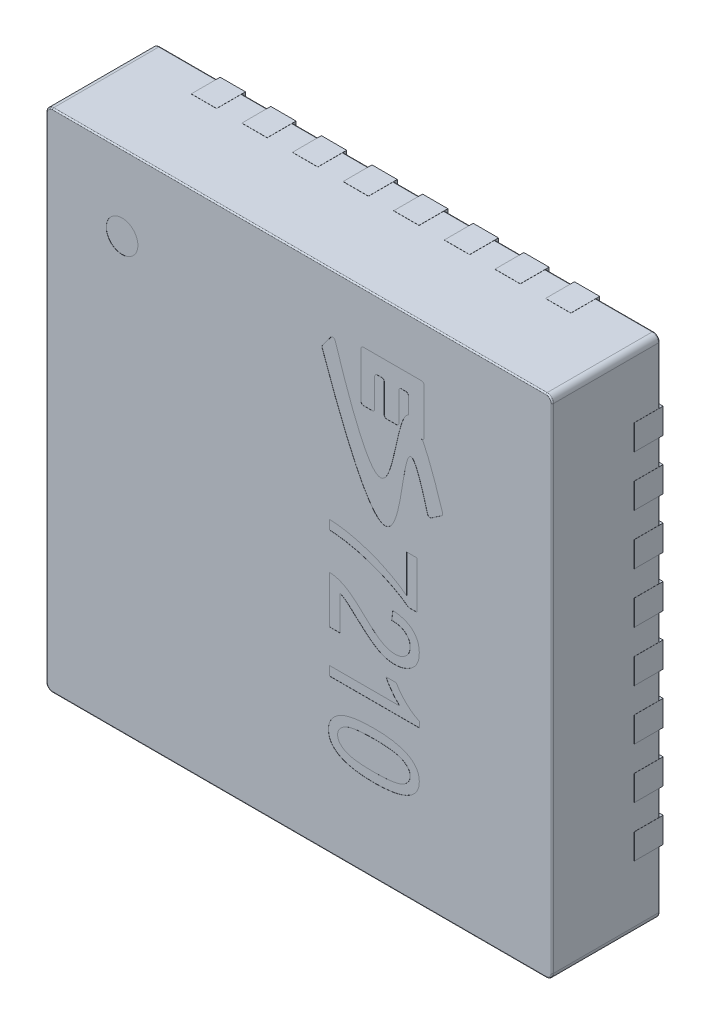
SolidWorks part; units mm, degrees
other "ES7210" parameters "D5"=0.3678, "D1"=3.1308, "D2"=3.0402, "D3"=0.4115, "D4"=0.3, "D6"=0.3296, "D7"=0.2637, "D8"=0.9806, "D10"=0.4, "D11"=0.25, "D9"=4
ref_plane "Front Plane" through (0, 0, 0) normal (0, 0, 1) x (1, 0, 0)
ref_plane "Top Plane" through (0, 0, 0) normal (0, 1, 0) x (1, 0, 0)
ref_plane "Right Plane" through (0, 0, 0) normal (1, 0, 0) x (0, 0, -1)
sketch "Sketch1" plane through (0, 0, 0) normal (0, 1, 0) x (1, 0, 0)
  line L1 (-2, -2) -> (2, -2)
  line L2 (-2, -2) -> (-2, 2)
  line L3 (-2, 2) -> (2, 2)
  line L4 (2, -2) -> (2, 2)
  line L5 (-2, -2) -> (2, 2) construction
  line L6 (-2, 2) -> (2, -2) construction
  point P0 (0, 0)
  dimension "D1" = 4
  dimension "D2" = 4
extrude "Boss-Extrude1" add sketch "Sketch1" along normal blind 0.85
fillet "Fillet1" radius 0.05 4 edges at (2, 0.425, -2) (2, 0.425, 2) (-2, 0.425, 2) (-2, 0.425, -2)
fillet "Fillet2" radius 0.01 16 edges at (1.9854, 0.85, 1.9854) (0, 0.85, 2) (-1.9854, 0.85, 1.9854) (-2, 0.85, 0) (-1.9854, 0.85, -1.9854) (0, 0.85, -2) (1.9854, 0.85, -1.9854) (2, 0.85, 0) (2, 0, 0) (1.9854, 0, -1.9854) (0, 0, -2) (1.9854, 0, 1.9854) (0, 0, 2) (-1.9854, 0, 1.9854) (-2, 0, 0) (-1.9854, 0, -1.9854)
sketch "Sketch2" plane through (0, 0, 0) normal (0, -1, 0) x (1, 0, 0)
  line L0 (1.1, 1.4) -> (1.4, 1.1)
  line L1 (-1.35, -1.4) -> (1.35, -1.4)
  line L2 (-1.4, -1.35) -> (-1.4, 1.35)
  line L3 (-1.35, 1.4) -> (1.1, 1.4)
  line L4 (1.4, -1.35) -> (1.4, 1.1)
  line L5 (-1.3854, -1.3854) -> (1.4, 1.4) construction
  line L6 (-1.3854, 1.3854) -> (1.3854, -1.3854) construction
  line L7 (1.1, 1.4) -> (1.4, 1.4) construction
  line L8 (1.4, 1.1) -> (1.4, 1.4) construction
  line L9 (-1.4, 1.4) -> (-1.35, 1.4) construction
  line L10 (-1.4, 1.4) -> (-1.3854, 1.3854) construction
  line L11 (-1.4, 1.35) -> (-1.4, 1.4) construction
  line L12 (-1.4, -1.4) -> (-1.4, -1.35) construction
  line L13 (-1.4, -1.4) -> (-1.3854, -1.3854) construction
  line L14 (-1.4, -1.4) -> (-1.35, -1.4) construction
  line L15 (1.4, -1.4) -> (1.4, -1.35) construction
  line L16 (1.3854, -1.3854) -> (1.4, -1.4) construction
  line L17 (1.35, -1.4) -> (1.4, -1.4) construction
  line L18 (0, -1000) -> (0, 49000) construction
  line L23 (-0.3, 2.001) -> (-0.1, 2.001)
  line L24 (-0.3, 2.001) -> (-0.3, 1.701)
  line L25 (-0.3, 1.701) -> (-0.1, 1.701)
  line L26 (-0.1, 2.001) -> (-0.1, 1.701)
  line L27 (-0.3, 2.001) -> (-0.1, 1.701) construction
  line L28 (-0.3, 1.701) -> (-0.1, 2.001) construction
  line L30 (-0.7, 2.001) -> (-0.7, 1.701)
  line L31 (-0.7, 2.001) -> (-0.5, 2.001)
  line L32 (-0.5, 2.001) -> (-0.5, 1.701)
  line L33 (-0.7, 1.701) -> (-0.5, 1.701)
  line L34 (-0.7, 1.701) -> (-0.5, 2.001) construction
  line L35 (-0.7, 2.001) -> (-0.5, 1.701) construction
  line L36 (-1.1, 2.001) -> (-1.1, 1.701)
  line L37 (-1.1, 2.001) -> (-0.9, 2.001)
  line L38 (-0.9, 2.001) -> (-0.9, 1.701)
  line L39 (-1.1, 1.701) -> (-0.9, 1.701)
  line L40 (-1.1, 1.701) -> (-0.9, 2.001) construction
  line L41 (-1.1, 2.001) -> (-0.9, 1.701) construction
  line L42 (-1.5, 2.001) -> (-1.5, 1.701)
  line L43 (-1.5, 2.001) -> (-1.3, 2.001)
  line L44 (-1.3, 2.001) -> (-1.3, 1.701)
  line L45 (-1.5, 1.701) -> (-1.3, 1.701)
  line L46 (-1.5, 1.701) -> (-1.3, 2.001) construction
  line L47 (-1.5, 2.001) -> (-1.3, 1.701) construction
  line L48 (-0.3, 2.001) -> (-0.7, 2.001) construction
  line L162 (-1000, 0) -> (49000, 0) construction
  line L163 (-2, 2) -> (2, 2) construction
  line L164 (0.3, 2.001) -> (0.7, 2.001) construction
  line L165 (1.5, 2.001) -> (1.3, 1.701) construction
  line L166 (1.5, 1.701) -> (1.3, 2.001) construction
  line L167 (1.1, 2.001) -> (0.9, 1.701) construction
  line L168 (1.1, 1.701) -> (0.9, 2.001) construction
  line L169 (0.7, 2.001) -> (0.5, 1.701) construction
  line L170 (0.7, 1.701) -> (0.5, 2.001) construction
  line L171 (0.3, 1.701) -> (0.1, 2.001) construction
  line L172 (0.3, 2.001) -> (0.1, 1.701) construction
  line L173 (1.5, 1.701) -> (1.3, 1.701)
  line L174 (1.3, 2.001) -> (1.3, 1.701)
  line L175 (1.5, 2.001) -> (1.3, 2.001)
  line L176 (1.5, 2.001) -> (1.5, 1.701)
  line L177 (1.1, 1.701) -> (0.9, 1.701)
  line L178 (0.9, 2.001) -> (0.9, 1.701)
  line L179 (1.1, 2.001) -> (0.9, 2.001)
  line L180 (1.1, 2.001) -> (1.1, 1.701)
  line L181 (0.7, 1.701) -> (0.5, 1.701)
  line L182 (0.5, 2.001) -> (0.5, 1.701)
  line L183 (0.7, 2.001) -> (0.5, 2.001)
  line L184 (0.7, 2.001) -> (0.7, 1.701)
  line L185 (0.1, 2.001) -> (0.1, 1.701)
  line L186 (0.3, 1.701) -> (0.1, 1.701)
  line L187 (0.3, 2.001) -> (0.3, 1.701)
  line L188 (0.3, 2.001) -> (0.1, 2.001)
  line L189 (0.3, -2.001) -> (0.1, -1.701) construction
  line L190 (0.3, -1.701) -> (0.1, -2.001) construction
  line L191 (0.7, -1.701) -> (0.5, -2.001) construction
  line L192 (0.7, -2.001) -> (0.5, -1.701) construction
  line L193 (1.1, -1.701) -> (0.9, -2.001) construction
  line L194 (1.1, -2.001) -> (0.9, -1.701) construction
  line L195 (1.5, -1.701) -> (1.3, -2.001) construction
  line L196 (1.5, -2.001) -> (1.3, -1.701) construction
  line L197 (0.3, -2.001) -> (0.7, -2.001) construction
  line L198 (-0.3, -2.001) -> (-0.7, -2.001) construction
  line L199 (-1.5, -2.001) -> (-1.3, -1.701) construction
  line L200 (-1.5, -1.701) -> (-1.3, -2.001) construction
  line L201 (-1.1, -2.001) -> (-0.9, -1.701) construction
  line L202 (-1.1, -1.701) -> (-0.9, -2.001) construction
  line L203 (-0.7, -2.001) -> (-0.5, -1.701) construction
  line L204 (-0.7, -1.701) -> (-0.5, -2.001) construction
  line L205 (-0.3, -1.701) -> (-0.1, -2.001) construction
  line L206 (-0.3, -2.001) -> (-0.1, -1.701) construction
  line L207 (0.3, -2.001) -> (0.1, -2.001)
  line L208 (0.3, -2.001) -> (0.3, -1.701)
  line L209 (0.3, -1.701) -> (0.1, -1.701)
  line L210 (0.1, -2.001) -> (0.1, -1.701)
  line L211 (0.7, -2.001) -> (0.7, -1.701)
  line L212 (0.7, -2.001) -> (0.5, -2.001)
  line L213 (0.5, -2.001) -> (0.5, -1.701)
  line L214 (0.7, -1.701) -> (0.5, -1.701)
  line L215 (1.1, -2.001) -> (1.1, -1.701)
  line L216 (1.1, -2.001) -> (0.9, -2.001)
  line L217 (0.9, -2.001) -> (0.9, -1.701)
  line L218 (1.1, -1.701) -> (0.9, -1.701)
  line L219 (1.5, -2.001) -> (1.5, -1.701)
  line L220 (1.5, -2.001) -> (1.3, -2.001)
  line L221 (1.3, -2.001) -> (1.3, -1.701)
  line L222 (1.5, -1.701) -> (1.3, -1.701)
  line L223 (-1.5, -1.701) -> (-1.3, -1.701)
  line L224 (-1.3, -2.001) -> (-1.3, -1.701)
  line L225 (-1.5, -2.001) -> (-1.3, -2.001)
  line L226 (-1.5, -2.001) -> (-1.5, -1.701)
  line L227 (-1.1, -1.701) -> (-0.9, -1.701)
  line L228 (-0.9, -2.001) -> (-0.9, -1.701)
  line L229 (-1.1, -2.001) -> (-0.9, -2.001)
  line L230 (-1.1, -2.001) -> (-1.1, -1.701)
  line L231 (-0.7, -1.701) -> (-0.5, -1.701)
  line L232 (-0.5, -2.001) -> (-0.5, -1.701)
  line L233 (-0.7, -2.001) -> (-0.5, -2.001)
  line L234 (-0.7, -2.001) -> (-0.7, -1.701)
  line L235 (-0.1, -2.001) -> (-0.1, -1.701)
  line L236 (-0.3, -1.701) -> (-0.1, -1.701)
  line L237 (-0.3, -2.001) -> (-0.3, -1.701)
  line L238 (-0.3, -2.001) -> (-0.1, -2.001)
  line L239 (2.001, 0.3) -> (1.701, 0.1) construction
  line L240 (1.701, 0.3) -> (2.001, 0.1) construction
  line L241 (1.701, 0.7) -> (2.001, 0.5) construction
  line L242 (2.001, 0.7) -> (1.701, 0.5) construction
  line L243 (1.701, 1.1) -> (2.001, 0.9) construction
  line L244 (2.001, 1.1) -> (1.701, 0.9) construction
  line L245 (1.701, 1.5) -> (2.001, 1.3) construction
  line L246 (2.001, 1.5) -> (1.701, 1.3) construction
  line L247 (2.001, 0.3) -> (2.001, 0.7) construction
  line L248 (2.001, -0.3) -> (2.001, -0.7) construction
  line L249 (2.001, -1.5) -> (1.701, -1.3) construction
  line L250 (1.701, -1.5) -> (2.001, -1.3) construction
  line L251 (2.001, -1.1) -> (1.701, -0.9) construction
  line L252 (1.701, -1.1) -> (2.001, -0.9) construction
  line L253 (2.001, -0.7) -> (1.701, -0.5) construction
  line L254 (1.701, -0.7) -> (2.001, -0.5) construction
  line L255 (1.701, -0.3) -> (2.001, -0.1) construction
  line L256 (2.001, -0.3) -> (1.701, -0.1) construction
  line L257 (2.001, 0.3) -> (2.001, 0.1)
  line L258 (2.001, 0.3) -> (1.701, 0.3)
  line L259 (1.701, 0.3) -> (1.701, 0.1)
  line L260 (2.001, 0.1) -> (1.701, 0.1)
  line L261 (2.001, 0.7) -> (1.701, 0.7)
  line L262 (2.001, 0.7) -> (2.001, 0.5)
  line L263 (2.001, 0.5) -> (1.701, 0.5)
  line L264 (1.701, 0.7) -> (1.701, 0.5)
  line L265 (2.001, 1.1) -> (1.701, 1.1)
  line L266 (2.001, 1.1) -> (2.001, 0.9)
  line L267 (2.001, 0.9) -> (1.701, 0.9)
  line L268 (1.701, 1.1) -> (1.701, 0.9)
  line L269 (2.001, 1.5) -> (1.701, 1.5)
  line L270 (2.001, 1.5) -> (2.001, 1.3)
  line L271 (2.001, 1.3) -> (1.701, 1.3)
  line L272 (1.701, 1.5) -> (1.701, 1.3)
  line L273 (1.701, -1.5) -> (1.701, -1.3)
  line L274 (2.001, -1.3) -> (1.701, -1.3)
  line L275 (2.001, -1.5) -> (2.001, -1.3)
  line L276 (2.001, -1.5) -> (1.701, -1.5)
  line L277 (1.701, -1.1) -> (1.701, -0.9)
  line L278 (2.001, -0.9) -> (1.701, -0.9)
  line L279 (2.001, -1.1) -> (2.001, -0.9)
  line L280 (2.001, -1.1) -> (1.701, -1.1)
  line L281 (1.701, -0.7) -> (1.701, -0.5)
  line L282 (2.001, -0.5) -> (1.701, -0.5)
  line L283 (2.001, -0.7) -> (2.001, -0.5)
  line L284 (2.001, -0.7) -> (1.701, -0.7)
  line L285 (2.001, -0.1) -> (1.701, -0.1)
  line L286 (1.701, -0.3) -> (1.701, -0.1)
  line L287 (2.001, -0.3) -> (1.701, -0.3)
  line L288 (2.001, -0.3) -> (2.001, -0.1)
  line L289 (-2.001, -0.3) -> (-1.701, -0.1) construction
  line L290 (-1.701, -0.3) -> (-2.001, -0.1) construction
  line L291 (-1.701, -0.7) -> (-2.001, -0.5) construction
  line L292 (-2.001, -0.7) -> (-1.701, -0.5) construction
  line L293 (-1.701, -1.1) -> (-2.001, -0.9) construction
  line L294 (-2.001, -1.1) -> (-1.701, -0.9) construction
  line L295 (-1.701, -1.5) -> (-2.001, -1.3) construction
  line L296 (-2.001, -1.5) -> (-1.701, -1.3) construction
  line L297 (-2.001, -0.3) -> (-2.001, -0.7) construction
  line L298 (-2.001, 0.3) -> (-2.001, 0.7) construction
  line L299 (-2.001, 1.5) -> (-1.701, 1.3) construction
  line L300 (-1.701, 1.5) -> (-2.001, 1.3) construction
  line L301 (-2.001, 1.1) -> (-1.701, 0.9) construction
  line L302 (-1.701, 1.1) -> (-2.001, 0.9) construction
  line L303 (-2.001, 0.7) -> (-1.701, 0.5) construction
  line L304 (-1.701, 0.7) -> (-2.001, 0.5) construction
  line L305 (-1.701, 0.3) -> (-2.001, 0.1) construction
  line L306 (-2.001, 0.3) -> (-1.701, 0.1) construction
  line L307 (-2.001, -0.3) -> (-2.001, -0.1)
  line L308 (-2.001, -0.3) -> (-1.701, -0.3)
  line L309 (-1.701, -0.3) -> (-1.701, -0.1)
  line L310 (-2.001, -0.1) -> (-1.701, -0.1)
  line L311 (-2.001, -0.7) -> (-1.701, -0.7)
  line L312 (-2.001, -0.7) -> (-2.001, -0.5)
  line L313 (-2.001, -0.5) -> (-1.701, -0.5)
  line L314 (-1.701, -0.7) -> (-1.701, -0.5)
  line L315 (-2.001, -1.1) -> (-1.701, -1.1)
  line L316 (-2.001, -1.1) -> (-2.001, -0.9)
  line L317 (-2.001, -0.9) -> (-1.701, -0.9)
  line L318 (-1.701, -1.1) -> (-1.701, -0.9)
  line L319 (-2.001, -1.5) -> (-1.701, -1.5)
  line L320 (-2.001, -1.5) -> (-2.001, -1.3)
  line L321 (-2.001, -1.3) -> (-1.701, -1.3)
  line L322 (-1.701, -1.5) -> (-1.701, -1.3)
  line L323 (-1.701, 1.5) -> (-1.701, 1.3)
  line L324 (-2.001, 1.3) -> (-1.701, 1.3)
  line L325 (-2.001, 1.5) -> (-2.001, 1.3)
  line L326 (-2.001, 1.5) -> (-1.701, 1.5)
  line L327 (-1.701, 1.1) -> (-1.701, 0.9)
  line L328 (-2.001, 0.9) -> (-1.701, 0.9)
  line L329 (-2.001, 1.1) -> (-2.001, 0.9)
  line L330 (-2.001, 1.1) -> (-1.701, 1.1)
  line L331 (-1.701, 0.7) -> (-1.701, 0.5)
  line L332 (-2.001, 0.5) -> (-1.701, 0.5)
  line L333 (-2.001, 0.7) -> (-2.001, 0.5)
  line L334 (-2.001, 0.7) -> (-1.701, 0.7)
  line L335 (-2.001, 0.1) -> (-1.701, 0.1)
  line L336 (-1.701, 0.3) -> (-1.701, 0.1)
  line L337 (-2.001, 0.3) -> (-1.701, 0.3)
  line L338 (-2.001, 0.3) -> (-2.001, 0.1)
  arc A0 (-1.35, 1.4) -> (-1.4, 1.35) centre (-1.35, 1.35) ccw
  arc A1 (-1.4, -1.35) -> (-1.35, -1.4) centre (-1.35, -1.35) ccw
  arc A2 (1.35, -1.4) -> (1.4, -1.35) centre (1.35, -1.35) ccw
  point P0 (0, 0)
  point P12 (-0.2, 1.851)
  point P60 (0.2, 1.851)
  point P93 (0.2, -1.851)
  point P94 (-0.2, -1.851)
  point P127 (1.851, 0.2)
  point P128 (1.851, -0.2)
  point P161 (-1.851, -0.2)
  point P162 (-1.851, 0.2)
  dimension "D5" = 0.1
  dimension "D1" = 2.8
  dimension "D2" = 2.8
  dimension "D4" = 45
  dimension "D6" = 0.3
  dimension "D7" = 0.2
  dimension "D8" = 0.2
  dimension "D11" = 0.001
  dimension "D3" = 0.3
extrude "Boss-Extrude2" add sketch "Sketch2" along normal blind 0.025 and the other way blind 0.203
sketch "Sketch3" plane through (0, 0.85, 0) normal (0, 1, 0) x (1, 0, 0)
  line L7 (26, 64) -> (130, 64) construction
  line L8 (-1.0138, -0.7053) -> (-0.6787, -1.9525) construction
  line L9 (1.95, -2) -> (-1.95, -2) construction
  line L10 (26, 64) -> (130, 64) construction
  line L11 (2, 1.95) -> (2, -1.95) construction
  line L24 (-0.9672, -1.5941) -> (-0.5072, -1.5941)
  line L25 (-0.6787, -1.9525) -> (-1.021, 0.95) construction
  line L26 (-0.4872, -1.5741) -> (-0.4872, -1.2141)
  line L27 (-0.5072, -1.1941) -> (-0.5767, -1.1941)
  line L28 (-0.5967, -1.2141) -> (-0.5967, -1.4388)
  line L29 (-0.6167, -1.4588) -> (-0.6517, -1.4588)
  line L30 (-0.6717, -1.4388) -> (-0.6717, -1.2141)
  line L31 (-0.6917, -1.1941) -> (-0.7672, -1.1941)
  line L32 (-0.7872, -1.2141) -> (-0.7872, -1.4388)
  line L33 (-0.8072, -1.4588) -> (-0.8422, -1.4588)
  line L34 (-0.8622, -1.4388) -> (-0.8622, -1.3074)
  line L35 (-0.9751, -1.1941) -> (-0.9672, -1.1941)
  line L36 (-0.9872, -1.2141) -> (-0.9872, -1.5741)
  line L37 (-1.021, 0.95) -> (-0.1811, -1.4264) construction
  line L38 (-1.1334, -0.7723) -> (-1.069, -0.9753) construction
  line L39 (-1.069, -0.9753) -> (-1.0173, -1.1102) construction
  line L40 (-1.0173, -1.1102) -> (-0.9751, -1.1941) construction
  line L41 (-1.1257, -0.7498) -> (-1.0444, -0.694)
  line L42 (-0.2492, -1.5332) -> (-0.1839, -1.4449)
  line L43 (-0.8822, -1.1941) -> (-0.9751, -1.1941) construction
  line L44 (-0.9751, -1.1941) -> (-0.9266, -1.2904) construction
  line L45 (-0.9266, -1.2904) -> (-0.8907, -1.3195) construction
  line L46 (-0.8907, -1.3195) -> (-0.8622, -1.3074) construction
  line L47 (-0.8622, -1.3074) -> (-0.71, -1.2427) construction
  line L48 (-0.71, -1.2427) -> (-0.7716, 0.001) construction
  line L49 (-0.7716, 0.001) -> (-0.2843, -1.5273) construction
  line L50 (-0.8622, -1.2694) -> (-0.8622, -1.2141) construction
  line L51 (-0.8622, -1.3074) -> (-0.8622, -1.2694) construction
  line L52 (-0.24, -0.4) -> (-0.24, 1.99) construction
  line L53 (1.95, 1.99) -> (-1.95, 1.99) construction
  line L54 (-1.99, 1.95) -> (-1.99, -1.95) construction
  circle A10 centre (1.4, -1.4) radius 0.125
  arc A11 (-0.1839, -1.4449) -> (-0.1811, -1.4264) centre (-0.2, -1.4331) ccw
  arc A12 (-0.2492, -1.5332) -> (-0.2843, -1.5273) centre (-0.2652, -1.5213) cw
  arc A13 (-1.0138, -0.7053) -> (-1.0444, -0.694) centre (-1.0331, -0.7105) ccw
  arc A14 (-1.1257, -0.7498) -> (-1.1334, -0.7723) centre (-1.1144, -0.7662) ccw
  arc A15 (-0.4872, -1.2141) -> (-0.5072, -1.1941) centre (-0.5072, -1.2141) ccw
  arc A16 (-0.5767, -1.1941) -> (-0.5967, -1.2141) centre (-0.5767, -1.2141) ccw
  arc A17 (-0.6167, -1.4588) -> (-0.5967, -1.4388) centre (-0.6167, -1.4388) ccw
  arc A18 (-0.6517, -1.4588) -> (-0.6717, -1.4388) centre (-0.6517, -1.4388) cw
  arc A19 (-0.6717, -1.2141) -> (-0.6917, -1.1941) centre (-0.6917, -1.2141) ccw
  arc A20 (-0.7672, -1.1941) -> (-0.7872, -1.2141) centre (-0.7672, -1.2141) ccw
  arc A21 (-0.5072, -1.5941) -> (-0.4872, -1.5741) centre (-0.5072, -1.5741) ccw
  arc A22 (-0.9672, -1.5941) -> (-0.9872, -1.5741) centre (-0.9672, -1.5741) cw
  arc A23 (-0.8072, -1.4588) -> (-0.7872, -1.4388) centre (-0.8072, -1.4388) ccw
  arc A24 (-0.8422, -1.4588) -> (-0.8622, -1.4388) centre (-0.8422, -1.4388) cw
  arc A25 (-0.8806, -1.1942) -> (-0.8822, -1.1941) centre (-0.8822, -1.2141) ccw construction
  arc A26 (-0.9672, -1.1941) -> (-0.9872, -1.2141) centre (-0.9672, -1.2141) ccw
  arc A27 (-0.8622, -1.2141) -> (-0.8806, -1.1942) centre (-0.8822, -1.2141) ccw construction
  spline S0 degree 3 poles (-1.0138, -0.7053) (-0.6787, -1.9525) (-1.021, 0.95) (-0.1811, -1.4264) knots 0 0 0 0 1 1 1 1
  spline S1 degree 3 poles (-1.1334, -0.7723) (-1.069, -0.9753) (-1.0173, -1.1102) (-0.9751, -1.1941) knots 0 0 0 0 1 1 1 1
  spline S2 degree 3 poles (-0.9751, -1.1941) (-0.9266, -1.2904) (-0.8907, -1.3195) (-0.8622, -1.3074) knots 0 0 0 0 1 1 1 1 construction
  spline S3 degree 3 poles (-0.8622, -1.3074) (-0.71, -1.2427) (-0.7716, 0.001) (-0.2843, -1.5273) knots 0 0 0 0 1 1 1 1
  text T0 "7210" font "Arial Narrow" height 0.7
  point P52 (-0.4872, -1.5941)
  point P55 (-0.9872, -1.5941)
  point P58 (-0.7872, -1.4588)
  point P61 (-0.8622, -1.4588)
  point P64 (-0.8622, -1.1941)
  point P67 (-0.9872, -1.1941)
  dimension "D2" = 0.25
  dimension "D8" = 0.02
  dimension "D3" = 0.6
  dimension "D4" = 0.6
  dimension "D9" = 1.75
  dimension "D10" = 1.6
extrude "Cut-Extrude1" cut sketch "Sketch3" against normal blind 0.001
move or copy body "Body-Move/Copy1" bodies to move or copy 131 copy no rotation origin (0, 0, 0) rotation axis (0, 0.7071, 0.7071) rotation angle 180
move or copy body "Body-Move/Copy2" bodies to move or copy 132 copy no translate (0, 0, 0.025)
equation "\"D8@Sketch2\"=\"D10@Sketch2\"/2"
equation "\"D4@Sketch3\"=\"D3@Sketch3\""
equation "\"D1@Sketch2\"=\"D2@Sketch2\""
equation "\"D1@Sketch1\"=\"D2@Sketch1\""
